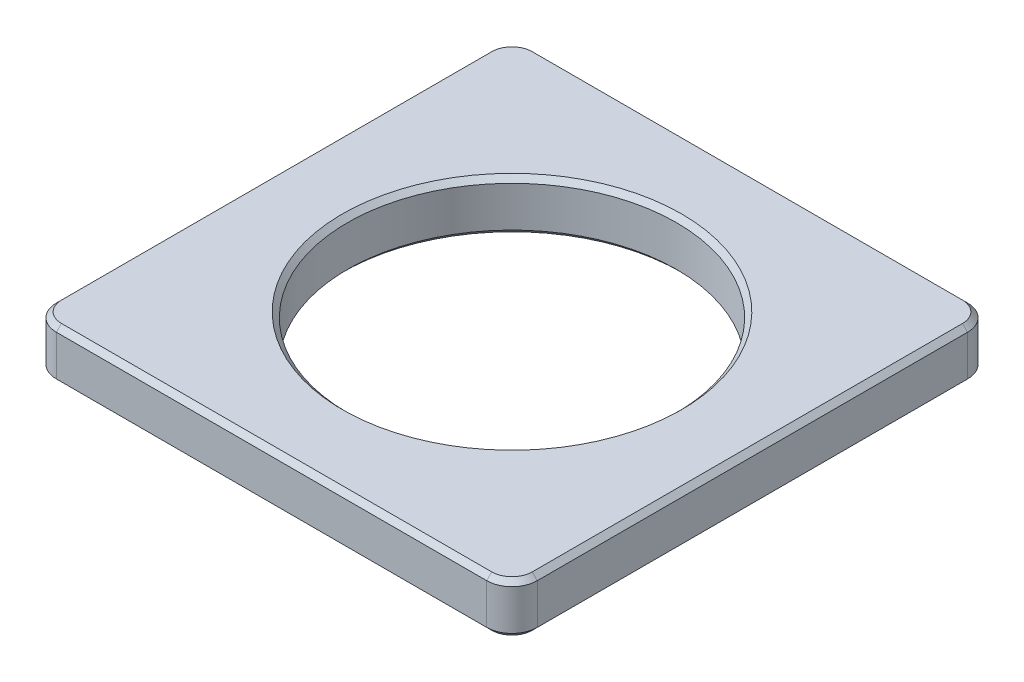
SolidWorks part; units mm, degrees
ref_plane "Front Plane" through (0, 0, 0) normal (0, 0, 1) x (1, 0, 0)
ref_plane "Top Plane" through (0, 0, 0) normal (0, 1, 0) x (1, 0, 0)
ref_plane "Right Plane" through (0, 0, 0) normal (1, 0, 0) x (0, 0, -1)
sketch "Sketch1" plane through (0, 0, 0) normal (0, 1, 0) x (1, 0, 0)
  line L1 (-47.5, -47.5) -> (47.5, -47.5)
  line L2 (-47.5, -47.5) -> (-47.5, 47.5)
  line L3 (-47.5, 47.5) -> (47.5, 47.5)
  line L4 (47.5, -47.5) -> (47.5, 47.5)
  line L5 (-47.5, -47.5) -> (47.5, 47.5) construction
  line L6 (-47.5, 47.5) -> (47.5, -47.5) construction
  circle A0 centre (0, 0) radius 32.5
  dimension "D1" = 65
  dimension "D2" = 95
extrude "Boss-Extrude1" add sketch "Sketch1" along normal blind 10 contours L3 L4 L1 L2
fillet "Fillet1" radius 5 4 edges at (-47.5, 5, -47.5) (47.5, 5, -47.5) (47.5, 5, 47.5) (-47.5, 5, 47.5)
chamfer "Chamfer1" distance 1 angle 45 18 edges at (0, 0, 32.5) (-46.0355, 0, 46.0355) (0, 0, 47.5) (46.0355, 0, 46.0355) (47.5, 0, 0) (46.0355, 0, -46.0355) (0, 0, -47.5) (-46.0355, 0, -46.0355) (-47.5, 0, 0) (0, 10, 32.5) (46.0355, 10, -46.0355) (47.5, 10, 0) (46.0355, 10, 46.0355) (0, 10, 47.5) (-46.0355, 10, 46.0355) (-47.5, 10, 0) (-46.0355, 10, -46.0355) (0, 10, -47.5)
